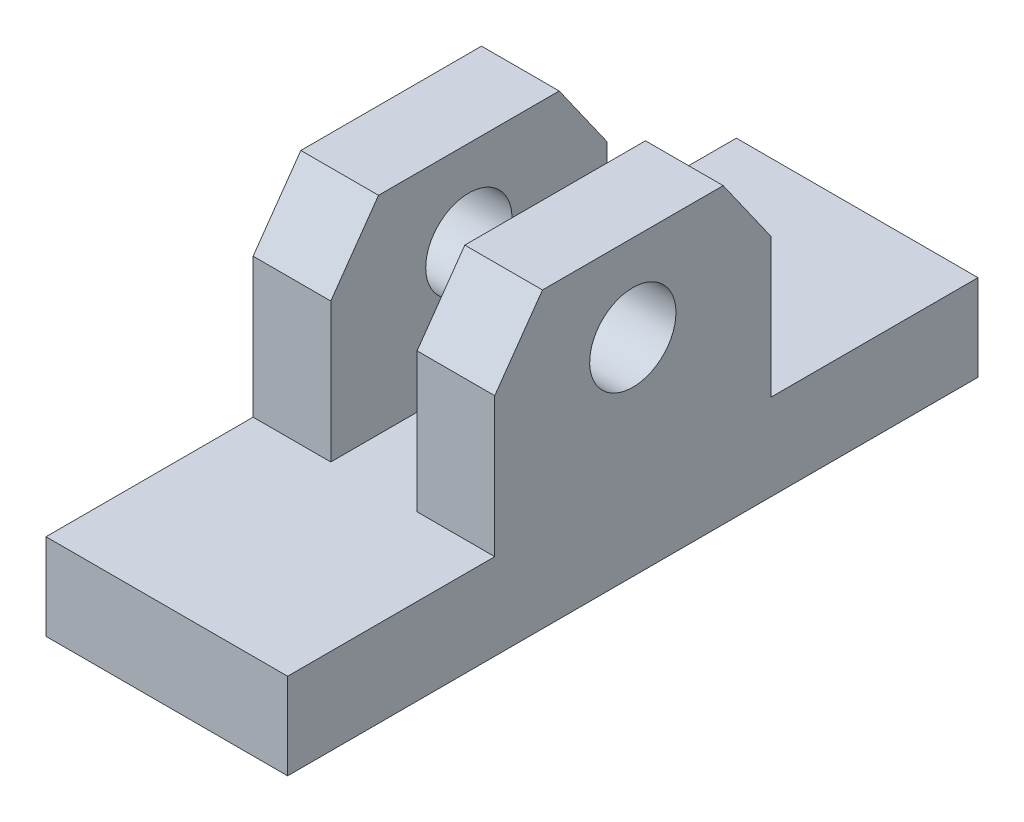
SolidWorks part; units mm, degrees
ref_plane "Спереди" through (0, 0, 0) normal (0, 0, 1) x (1, 0, 0)
ref_plane "Сверху" through (0, 0, 0) normal (0, 1, 0) x (1, 0, 0)
ref_plane "Справа" through (0, 0, 0) normal (1, 0, 0) x (0, 0, -1)
sketch "Эскиз2" plane through (0, 0, 0) normal (1, 0, 0) x (0, 0, -1)
  line L0 (0, 0) -> (40, 0)
  line L1 (0, 0) -> (0, 5)
  line L2 (20, 0) -> (20, 30.2856) construction
  line L3 (0, 5) -> (12, 5)
  line L4 (12, 5) -> (12, 13.0775)
  line L5 (14.7651, 17) -> (25.2349, 17)
  line L6 (12, 13.0775) -> (14.7651, 17)
  line L7 (28, 13.0775) -> (25.2349, 17)
  line L8 (28, 5) -> (28, 13.0775)
  line L9 (40, 5) -> (28, 5)
  line L10 (40, 0) -> (40, 5)
  circle A0 centre (20, 12) radius 2.5
  point P11 (20, 17)
  dimension "D1" = 12
  dimension "D2" = 17
  dimension "D3" = 20
extrude "Вытянуть1" add sketch "Эскиз2" along normal blind 14
sketch "Эскиз3" plane through (0, 0, -12) normal (0, 0, 1) x (1, 0, 0)
  line L0 (14, 17) -> (0, 17) construction
  line L3 (4.5007, 29) -> (9.4993, 29)
  line L4 (4.5007, 29) -> (4.5007, 5)
  line L5 (4.5007, 5) -> (9.4993, 5)
  line L6 (9.4993, 29) -> (9.4993, 5)
  line L7 (4.5007, 29) -> (9.4993, 5) construction
  line L8 (4.5007, 5) -> (9.4993, 29) construction
  line L10 (14, 5) -> (0, 5) construction
  point P0 (7, 17)
extrude "Вытянуть2" cut sketch "Эскиз3" against normal blind 16
